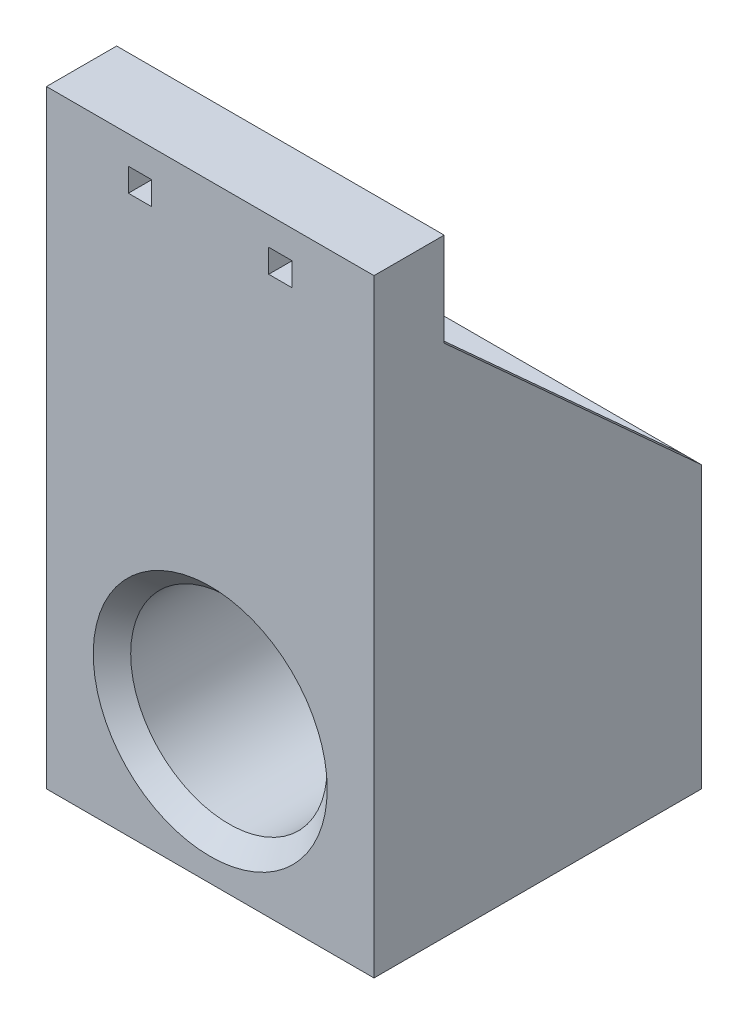
SolidWorks part; units mm, degrees
ref_plane "Front Plane" through (0, 0, 0) normal (0, 0, 1) x (1, 0, 0)
ref_plane "Top Plane" through (0, 0, 0) normal (0, 1, 0) x (1, 0, 0)
ref_plane "Right Plane" through (0, 0, 0) normal (1, 0, 0) x (0, 0, -1)
sketch "Sketch1" plane through (0, 0, 0) normal (1, 0, 0) x (0, 0, -1)
  line L1 (-35, 30) -> (35, 30)
  line L2 (-35, 30) -> (-35, -30)
  line L3 (-35, -30) -> (35, -30)
  line L4 (35, 30) -> (35, -30)
  line L5 (-35, 30) -> (35, -30) construction
  line L6 (-35, -30) -> (35, 30) construction
  line L7 (-35, 30) -> (-30, 30)
  line L8 (-35, 30) -> (-35, 100)
  line L9 (-35, 100) -> (-30, 100)
  line L10 (-30, 30) -> (-30, 100)
  point P0 (0, 0)
  dimension "D1" = 70
  dimension "D2" = 60
  dimension "D3" = 70
  dimension "D4" = 5
extrude "Boss-Extrude1" add sketch "Sketch1" along normal mid plane 70 contours L1 L10 L9 L8 | L4 L1 L2 L3
sketch "Sketch2" plane through (0, 0, -35) normal (0, 0, -1) x (-1, 0, 0)
  circle A0 centre (0, 0) radius 21
  dimension "D1" = 42
extrude "Cut-Extrude1" cut sketch "Sketch2" against normal through all
chamfer "Chamfer1" distance 4 angle 45 1 edges at (-21, 0, 35)
chamfer "Chamfer2" distance 4 angle 45 1 edges at (-21, 0, -35)
sketch "Sketch9" plane through (35, 0, 0) normal (1, 0, 0) x (0, 0, -1)
  line L1 (-30, 100) -> (-20, 100)
  line L2 (-30, 100) -> (-30, 80)
  line L3 (-30, 80) -> (-20, 80)
  line L4 (-20, 100) -> (-20, 80)
  dimension "D1" = 10
  dimension "D2" = 20
extrude "Boss-Extrude2" add sketch "Sketch9" against normal through all
sketch "Sketch10" plane through (35, 0, 0) normal (1, 0, 0) x (0, 0, -1)
  line L0 (-20, 80) -> (35, 30)
rib "Rib1" sketch "Sketch10" sketch "Sketch10" thickness 4 extrusion direction parallel to sketch draft on no parameters "D1"=4
mirror "Mirror1" about plane through (0, 0, 0) normal (1, 0, 0) of "Rib1"
sketch "Sketch11" plane through (0, 0, 35) normal (0, 0, 1) x (1, 0, 0)
  line L0 (-15, 91.5) -> (15, 91.5) construction
  line L1 (17.5, 94) -> (12.5, 94)
  line L2 (17.5, 94) -> (17.5, 89)
  line L3 (17.5, 89) -> (12.5, 89)
  line L4 (12.5, 94) -> (12.5, 89)
  line L5 (17.5, 94) -> (12.5, 89) construction
  line L6 (17.5, 89) -> (12.5, 94) construction
  line L7 (-12.5, 94) -> (-17.5, 94)
  line L8 (-12.5, 94) -> (-12.5, 89)
  line L9 (-12.5, 89) -> (-17.5, 89)
  line L10 (-17.5, 94) -> (-17.5, 89)
  line L11 (-12.5, 94) -> (-17.5, 89) construction
  line L12 (-12.5, 89) -> (-17.5, 94) construction
  line L14 (35, 100) -> (-35, 100) construction
  point P0 (15, 91.5)
  point P5 (-15, 91.5)
  point P10 (0, 91.5)
  point P16 (0, 0)
  dimension "D1" = 5
  dimension "D2" = 30
  dimension "D3" = 6
extrude "Cut-Extrude2" cut sketch "Sketch11" against normal blind 10 contours L2 L3 L4 L1 | L7 L10 L9 L8
